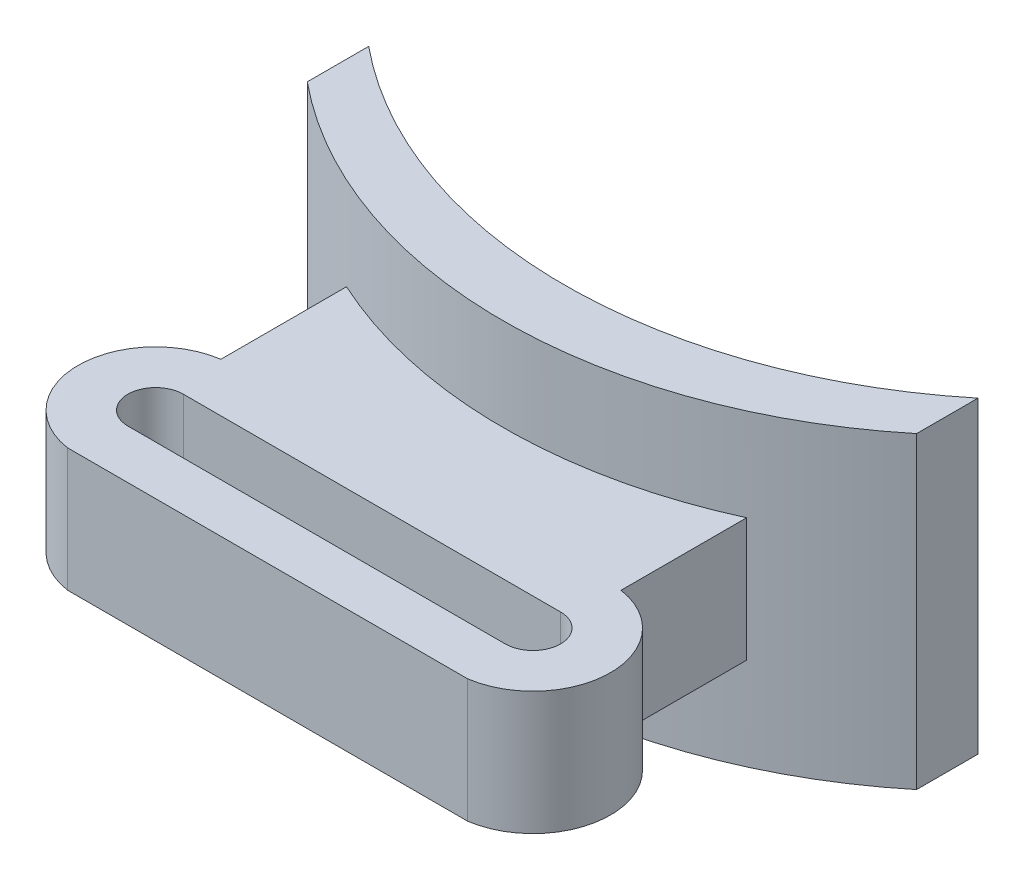
SolidWorks part; units mm, degrees
ref_plane "Front Plane" through (0, 0, 0) normal (0, 0, 1) x (1, 0, 0)
ref_plane "Top Plane" through (0, 0, 0) normal (0, 1, 0) x (1, 0, 0)
ref_plane "Right Plane" through (0, 0, 0) normal (1, 0, 0) x (0, 0, -1)
sketch "Sketch2" plane through (0, 0, 0) normal (0, 1, 0) x (1, 0, 0)
  line L0 (-6.2745, 2.2405) -> (-6.2745, 0.9761)
  line L1 (6.2745, 2.2405) -> (6.2745, 0.9761)
  arc A0 (-6.2745, 0.9761) -> (6.2745, 0.9761) centre (0, 8.617) ccw
  arc A1 (-6.2745, 2.2405) -> (6.2745, 2.2405) centre (0, 9.906) ccw
  point P5 (0, -1.27)
  point P12 (0, 0)
  dimension "D3" = 9.887
  dimension "D5" = 9.906
  dimension "D1" = 6.35
  dimension "D2" = 6.35
  dimension "D4" = 1.27
extrude "Boss-Extrude1" add sketch "Sketch2" against normal mid plane 6.35
sketch "Sketch3" plane through (0, 0, 0) normal (0, 1, 0) x (1, 0, 0)
  line L1 (-4.1203, -0.3705) -> (4.1203, -0.3705)
  line L2 (-4.1203, -0.3705) -> (-4.1203, -2.9574)
  line L4 (4.1203, -0.3705) -> (4.1203, -2.9574)
  line L6 (-4.1203, -6.1159) -> (4.1203, -6.1159)
  arc A0 (-6.2745, 0.9761) -> (6.2745, 0.9761) centre (0, 8.617) ccw construction
  arc A1 (-4.1203, -2.9574) -> (-4.1203, -6.1159) centre (-3.8856, -4.5367) ccw
  arc A2 (4.1203, -6.1159) -> (4.1203, -2.9574) centre (3.8856, -4.5367) ccw
  point P13 (0, -0.3705)
  point P14 (0, -4.5367)
  point P15 (0, -6.1159)
  dimension "D1" = 8.2407
  dimension "D2" = 1.5966
  dimension "D4" = 5.7454
  dimension "D3" = 7.7712
  dimension "D5" = 2.5869
  dimension "D6" = 4.1203
extrude "Boss-Extrude2" add sketch "Sketch3" along normal mid plane 2.54
sketch "Sketch4" plane through (0, 1.27, 0) normal (0, 1, 0) x (1, 0, 0)
  line L0 (-3.8856, -4.5367) -> (3.8856, -4.5367) construction
  line L1 (-3.8856, -3.9669) -> (3.8856, -3.9669)
  line L2 (-3.8856, -5.1064) -> (3.8856, -5.1064)
  arc A0 (-3.8856, -3.9669) -> (-3.8856, -5.1064) centre (-3.8856, -4.5367) ccw
  arc A1 (3.8856, -5.1064) -> (3.8856, -3.9669) centre (3.8856, -4.5367) ccw
  point P4 (0, -4.5367)
  dimension "D1" = 0.5697
extrude "Cut-Extrude1" cut sketch "Sketch4" against normal through all
scale "Scale1" scale about centroid uniform scaling yes scale factor 2.5
